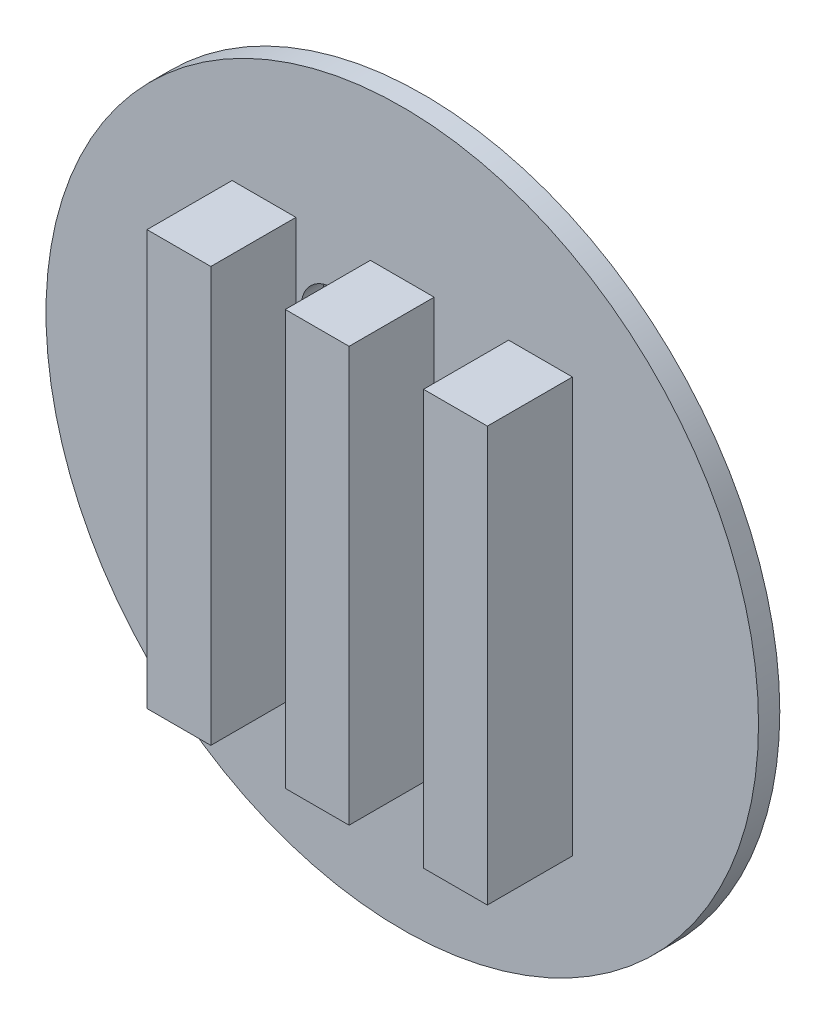
SolidWorks part; units mm, degrees
ref_plane "Front" through (0, 0, 0) normal (0, 0, 1) x (1, 0, 0)
ref_plane "Top" through (0, 0, 0) normal (0, 1, 0) x (1, 0, 0)
ref_plane "Right" through (0, 0, 0) normal (1, 0, 0) x (0, 0, -1)
sketch "Sketch1" plane through (0, 0, 0) normal (0, 0, 1) x (1, 0, 0)
  circle A0 centre (0, 0) radius 16.75
  dimension "D1" = 33.5
extrude "Extrude1" add sketch "Sketch1" along normal blind 1
ref_plane "Plane1" through (0, 0, 1) normal (0, 0, 1) x (1, 0, 0)
sketch "Sketch3" plane through (0, 0, 1) normal (0, 0, 1) x (1, 0, 0)
  line L0 (5, 9.75) -> (5, -9.75)
  line L1 (-1.5, 9.75) -> (1.5, 9.75)
  line L2 (-1.5, 9.75) -> (-1.5, -9.75)
  line L3 (-1.5, -9.75) -> (1.5, -9.75)
  line L4 (1.5, 9.75) -> (1.5, -9.75)
  line L5 (5, 9.75) -> (8, 9.75)
  line L6 (8, 9.75) -> (8, -9.75)
  line L7 (5, -9.75) -> (8, -9.75)
  line L8 (-8, 9.75) -> (-8, -9.75)
  line L9 (-8, 9.75) -> (-5, 9.75)
  line L10 (-5, 9.75) -> (-5, -9.75)
  line L11 (-8, -9.75) -> (-5, -9.75)
  line L12 (-1.5, 9.75) -> (-1.5, -9.75) [skipped]
  line L13 (-1.5, 9.75) -> (1.5, 9.75) [skipped]
  line L14 (1.5, 9.75) -> (1.5, -9.75) [skipped]
  line L15 (-1.5, -9.75) -> (1.5, -9.75) [skipped]
  line L16 (-1.5, 9.75) -> (5, 9.75) construction
  line L17 (-1.5, 9.75) -> (-8, 9.75) construction
  dimension "D1" = 3
  dimension "D2" = 19.5
  dimension "D3" = 9.75
  dimension "D4" = 1.5
extrude "Extrude4" add sketch "Sketch3" along normal blind 4
sketch "Sketch4" plane through (0, 0, 0) normal (0, 0, 1) x (1, 0, 0)
  line L0 (5.5, 9.75) -> (5.5, -9.75)
  line L1 (7.5, 9.75) -> (5.5, 9.75)
  line L2 (7.5, -9.75) -> (7.5, 9.75)
  line L3 (5.5, -9.75) -> (7.5, -9.75)
  line L4 (-7.5, 9.75) -> (-7.5, -9.75)
  line L5 (-5.5, 9.75) -> (-7.5, 9.75)
  line L6 (-5.5, -9.75) -> (-5.5, 9.75)
  line L7 (-7.5, -9.75) -> (-5.5, -9.75)
  line L8 (-1, 9.75) -> (-1, -9.75) [skipped]
  line L9 (1, 9.75) -> (-1, 9.75) [skipped]
  line L10 (1, -9.75) -> (1, 9.75) [skipped]
  line L11 (-1, -9.75) -> (1, -9.75) [skipped]
  line L12 (-1, 9.75) -> (5.5, 9.75) construction
  line L13 (-1, 9.75) -> (-7.5, 9.75) construction
  line L16 (-1, 9.75) -> (-1, -9.75)
  line L17 (-1, -9.75) -> (1, -9.75)
  line L18 (1, -9.75) -> (1, 9.75)
  line L19 (1, 9.75) -> (-1, 9.75)
  dimension "D4" = 1
  dimension "D1" = 2
  dimension "D2" = 19.5
  dimension "D3" = 9.75
extrude "Extrude5" add sketch "Sketch4" against normal blind 2
sketch "Sketch5" plane through (0, 0, 0) normal (0, 0, 1) x (1, 0, 0)
  circle A0 centre (-3.25, 6.25) radius 1.5
  circle A1 centre (3.25, -6.2624) radius 1.5
  dimension "D1" = 3
  dimension "D2" = 3
  dimension "D3" = 3.25
  dimension "D4" = 3.25
  dimension "D7" = 14.1
extrude "Cut-Extrude1" cut sketch "Sketch5" along normal blind 2
sketch "Sketch6" plane through (0, 0, 1) normal (0, 0, 1) x (1, 0, 0)
  line L0 (3.25, -6.2624) -> (3.25, 11.2041)
  line L1 (-3.25, 6.25) -> (17.3953, 6.25)
  line L2 (-3.25, 6.25) -> (3.25, -6.2624)
  line L3 (1, 8.2113) -> (1, -5.7049)
  line L4 (1, -9.75) -> (1, 9.75) construction
  line L5 (1, -9.75) -> (1, 9.75) construction
  dimension "D1" = 27.451
equation "\"D3@Sketch3\" = \"D2@Sketch3\" / 2"
equation "\"D4@Sketch3\" = \"D1@Sketch3\" / 2"
equation "\"D3@Sketch4\" = \"D2@Sketch4\"/2"
equation "\"D4@Sketch4\" = \"D1@Sketch4\" / 2"
